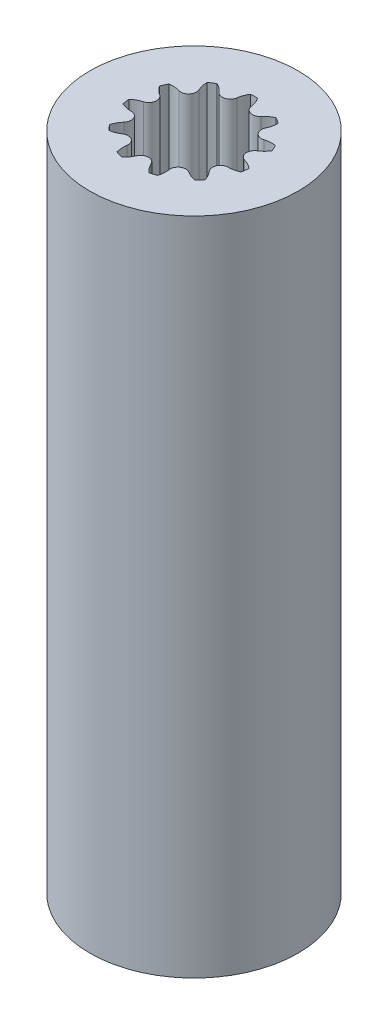
SolidWorks part; units mm, degrees
ref_plane "Front Plane" through (0, 0, 0) normal (0, 0, 1) x (1, 0, 0)
ref_plane "Top Plane" through (0, 0, 0) normal (0, 1, 0) x (1, 0, 0)
ref_plane "Right Plane" through (0, 0, 0) normal (1, 0, 0) x (0, 0, -1)
sketch "Sketch1" plane through (0, 0, 0) normal (0, 1, 0) x (1, 0, 0)
  circle A0 centre (0, 0) radius 4.5
  arc A1 (-0.9099, -1.9911) -> (-0.9065, -1.9578) centre (-1.2467, -1.9399) ccw
  arc A2 (-0.2959, -2.137) -> (-0.311, -2.1669) centre (0, -2.306) ccw
  arc A3 (0.2959, -2.137) -> (-0.2959, -2.137) centre (0, -2.306) ccw
  arc A4 (0.311, -2.1669) -> (0.2959, -2.137) centre (0, -2.306) ccw
  arc A5 (0.9065, -1.9578) -> (0.9099, -1.9911) centre (1.2467, -1.9399) ccw
  arc A6 (1.4332, -1.6548) -> (1.4043, -1.6378) centre (1.2467, -1.9399) ccw
  arc A7 (2.1003, -0.6172) -> (2.0668, -0.6186) centre (2.0976, -0.9579) ccw
  arc A8 (1.821, -1.1569) -> (1.8419, -1.1831) centre (2.0976, -0.9579) ccw
  arc A9 (2.1574, 0.0113) -> (2.1891, 0.0005) centre (2.2825, 0.3282) ccw
  arc A10 (2.1006, 0.6163) -> (2.0732, 0.597) centre (2.2825, 0.3282) ccw
  arc A11 (2.1003, -0.6172) -> (2.5472, -0.5215) centre (2.1087, 0.4352) ccw
  arc A12 (2.0668, -0.6186) -> (1.821, -1.1569) centre (2.0976, -0.9579) ccw
  arc A13 (2.0622, -1.5835) -> (1.8419, -1.1831) centre (1.052, -1.8786) ccw
  arc A14 (1.8609, -1.8159) -> (2.0622, -1.5835) centre (0, 0) ccw
  arc A15 (1.4332, -1.6548) -> (1.8609, -1.8159) centre (2.0092, -0.7739) ccw
  arc A16 (1.4043, -1.6378) -> (0.9065, -1.9578) centre (1.2467, -1.9399) ccw
  arc A17 (0.8787, -2.4471) -> (0.9099, -1.9911) centre (-0.1307, -2.1491) ccw
  arc A18 (0.5837, -2.5337) -> (0.8787, -2.4471) centre (0, 0) ccw
  arc A19 (0.311, -2.1669) -> (0.5837, -2.5337) centre (1.2719, -1.7373) ccw
  arc A20 (-0.5837, -2.5337) -> (-0.311, -2.1669) centre (-1.2719, -1.7373) ccw
  arc A21 (-0.8787, -2.4471) -> (-0.5837, -2.5337) centre (0, 0) ccw
  arc A22 (-0.9099, -1.9911) -> (-0.8787, -2.4471) centre (0.1307, -2.1491) ccw
  arc A23 (2.5472, -0.5215) -> (2.591, -0.2172) centre (0, 0) ccw
  arc A24 (2.591, -0.2172) -> (2.1891, 0.0005) centre (1.9006, -1.0117) ccw
  arc A25 (2.0732, 0.597) -> (2.1574, 0.0113) centre (2.2825, 0.3282) ccw
  arc A26 (2.1006, 0.6163) -> (2.4248, 0.9384) centre (1.5386, 1.5062) ccw
  arc A27 (2.4248, 0.9384) -> (2.2971, 1.2181) centre (0, 0) ccw
  arc A28 (-1.4043, -1.6378) -> (-1.4332, -1.6548) centre (-1.2467, -1.9399) ccw
  arc A29 (-1.8419, -1.1831) -> (-1.821, -1.1569) centre (-2.0976, -0.9579) ccw
  arc A30 (-2.0668, -0.6186) -> (-2.1003, -0.6172) centre (-2.0976, -0.9579) ccw
  arc A31 (-2.1891, 0.0005) -> (-2.1574, 0.0113) centre (-2.2825, 0.3282) ccw
  arc A32 (-2.0732, 0.597) -> (-2.1006, 0.6163) centre (-2.2825, 0.3282) ccw
  arc A33 (-0.9065, -1.9578) -> (-1.4043, -1.6378) centre (-1.2467, -1.9399) ccw
  arc A34 (-1.8609, -1.8159) -> (-1.4332, -1.6548) centre (-2.0092, -0.7739) ccw
  arc A35 (-2.0622, -1.5835) -> (-1.8609, -1.8159) centre (0, 0) ccw
  arc A36 (-1.8419, -1.1831) -> (-2.0622, -1.5835) centre (-1.052, -1.8786) ccw
  arc A37 (-1.821, -1.1569) -> (-2.0668, -0.6186) centre (-2.0976, -0.9579) ccw
  arc A38 (-2.5472, -0.5215) -> (-2.1003, -0.6172) centre (-2.1087, 0.4352) ccw
  arc A39 (-2.591, -0.2172) -> (-2.5472, -0.5215) centre (0, 0) ccw
  arc A40 (-2.1891, 0.0005) -> (-2.591, -0.2172) centre (-1.9006, -1.0117) ccw
  arc A41 (-2.1574, 0.0113) -> (-2.0732, 0.597) centre (-2.2825, 0.3282) ccw
  arc A42 (-2.4248, 0.9384) -> (-2.1006, 0.6163) centre (-1.5386, 1.5062) ccw
  arc A43 (-1.8413, 1.184) -> (-1.8088, 1.1759) centre (-1.7428, 1.5101) ccw
  arc A44 (-1.4213, 1.6231) -> (-1.434, 1.6541) centre (-1.7428, 1.5101) ccw
  arc A45 (-0.9089, 1.9915) -> (-0.886, 1.9671) centre (-0.6497, 2.2126) ccw
  arc A46 (-0.3182, 2.1338) -> (-0.3121, 2.1668) centre (-0.6497, 2.2126) ccw
  arc A47 (1.8088, 1.1759) -> (1.8413, 1.184) centre (1.7428, 1.5101) ccw
  arc A48 (1.434, 1.6541) -> (1.4213, 1.6231) centre (1.7428, 1.5101) ccw
  arc A49 (2.2971, 1.2181) -> (1.8413, 1.184) centre (2.1459, 0.1765) ccw
  arc A50 (1.4213, 1.6231) -> (1.8088, 1.1759) centre (1.7428, 1.5101) ccw
  arc A51 (1.434, 1.6541) -> (1.5326, 2.1004) centre (0.4801, 2.0989) ccw
  arc A52 (1.5326, 2.1004) -> (1.2739, 2.2666) centre (0, 0) ccw
  arc A53 (0.886, 1.9671) -> (0.9089, 1.9915) centre (0.6497, 2.2126) ccw
  arc A54 (0.3121, 2.1668) -> (0.3182, 2.1338) centre (0.6497, 2.2126) ccw
  arc A55 (1.2739, 2.2666) -> (0.9089, 1.9915) centre (1.7098, 1.3086) ccw
  arc A56 (0.3182, 2.1338) -> (0.886, 1.9671) centre (0.6497, 2.2126) ccw
  arc A57 (0.3121, 2.1668) -> (0.1537, 2.5955) centre (-0.7309, 2.0253) ccw
  arc A58 (0.1537, 2.5955) -> (0, 2.6001) centre (0, 0) ccw
  arc A59 (0, 2.6001) -> (-0.1537, 2.5955) centre (0, 0) ccw
  arc A60 (-0.1537, 2.5955) -> (-0.3121, 2.1668) centre (0.7309, 2.0253) ccw
  arc A61 (-0.886, 1.9671) -> (-0.3182, 2.1338) centre (-0.6497, 2.2126) ccw
  arc A62 (-0.9089, 1.9915) -> (-1.2739, 2.2666) centre (-1.7098, 1.3086) ccw
  arc A63 (-1.2739, 2.2666) -> (-1.5326, 2.1004) centre (0, 0) ccw
  arc A64 (-1.5326, 2.1004) -> (-1.434, 1.6541) centre (-0.4801, 2.0989) ccw
  arc A65 (-1.8088, 1.1759) -> (-1.4213, 1.6231) centre (-1.7428, 1.5101) ccw
  arc A66 (-1.8413, 1.184) -> (-2.2971, 1.2181) centre (-2.1459, 0.1765) ccw
  arc A67 (-2.2971, 1.2181) -> (-2.4248, 0.9384) centre (0, 0) ccw
  circle A68 centre (0, 0) radius 0.7859 construction
  circle A69 centre (0, 0) radius 1.8897 construction
  circle A70 centre (0, 0) radius 2.6001 construction
  dimension "D1" = 9
extrude "Boss-Extrude1" add sketch "Sketch1" along normal blind 8
sketch "Sketch2" plane through (0, 0, 0) normal (0, -1, 0) x (1, 0, 0)
  circle A0 centre (0, 0) radius 2.175
  circle A1 centre (0, 0) radius 4.5
  dimension "D1" = 4.35
  dimension "D2" = 9
extrude "Boss-Extrude2" add sketch "Sketch2" along normal blind 6
sketch "Sketch3" plane through (0, -6, 0) normal (0, -1, 0) x (1, 0, 0)
  circle A0 centre (0, 0) radius 4.5
  dimension "D1" = 9
extrude "Boss-Extrude3" add sketch "Sketch3" along normal blind 1.5
sketch "Sketch4" plane through (0, -7.5, 0) normal (0, -1, 0) x (1, 0, 0)
  line L0 (-1.7471, 2.5) -> (1.7471, 2.5)
  circle A1 centre (0, 0) radius 3.05
  circle A2 centre (0, 0) radius 4.5
  circle M4 centre (0, 0) radius 4.5
  dimension "D1" = 6.1
  dimension "D3" = 9
  dimension "D2" = 2.5
extrude "Boss-Extrude4" add sketch "Sketch4" along normal blind 13 contours L0 A1 | A1 M4
